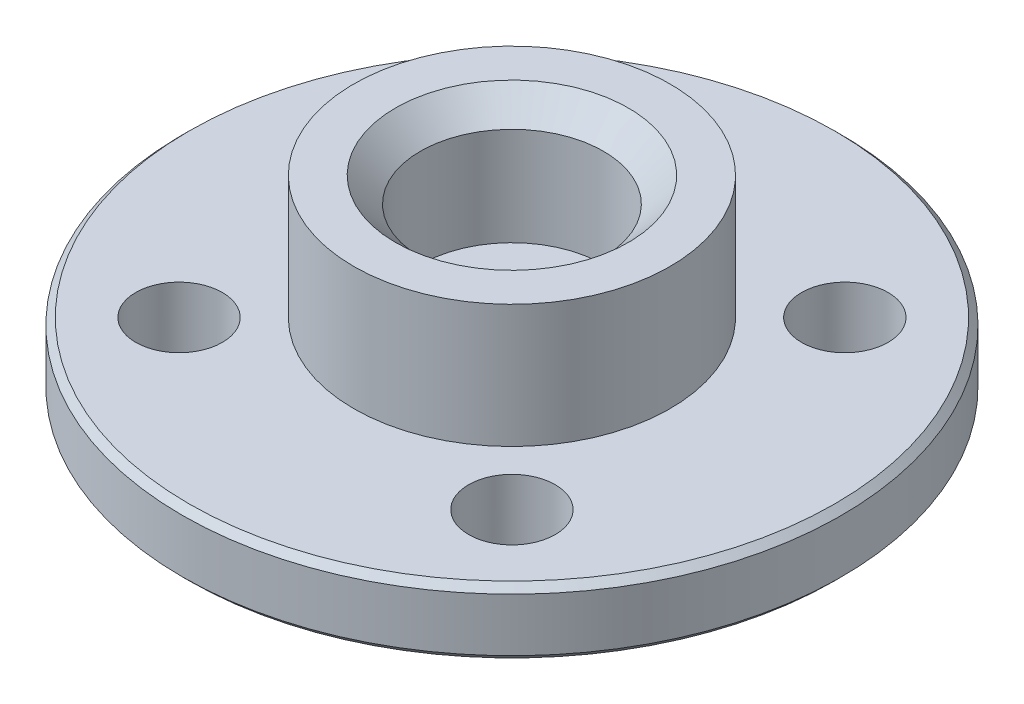
SolidWorks part; units mm, degrees
ref_plane "Front Plane" through (0, 0, 0) normal (0, 0, 1) x (1, 0, 0)
ref_plane "Top Plane" through (0, 0, 0) normal (0, 1, 0) x (1, 0, 0)
ref_plane "Right Plane" through (0, 0, 0) normal (1, 0, 0) x (0, 0, -1)
sketch "Sketch1" plane through (0, 0, 0) normal (0, 1, 0) x (1, 0, 0)
  circle A0 centre (0, 0) radius 9.9
  dimension "D1" = 19.8
extrude "Boss-Extrude1" add sketch "Sketch1" along normal blind 2 contours A0
sketch "Sketch2" plane through (0, 2, 0) normal (0, 1, 0) x (1, 0, 0)
  circle A0 centre (0, 0) radius 4.75
  circle A1 centre (0, 0) radius 2.75
  dimension "D1" = 9.5
  dimension "D2" = 5.5
extrude "Boss-Extrude2" add sketch "Sketch2" along normal blind 3.7
sketch "Sketch3" plane through (0, 0, 0) normal (0, -1, 0) x (1, 0, 0)
  line L0 (-5, 5) -> (5, -5) construction
  line L1 (5, 5) -> (-5, -5) construction
  circle A0 centre (-5, 5) radius 1.3
  circle A1 centre (5, 5) radius 1.3
  circle A2 centre (-5, -5) radius 1.3
  circle A3 centre (5, -5) radius 1.3
  circle A4 centre (0, 0) radius 1.45
  point P11 (0, 0)
  dimension "D1" = 2.9
  dimension "D2" = 2.6
  dimension "D3" = 10
  dimension "D4" = 10
extrude "Cut-Extrude1" cut sketch "Sketch3" against normal up to next
chamfer "Chamfer1" distance 0.75 angle 45 1 edges at (0, 5.7, 2.75)
chamfer "Chamfer2" distance 0.2 angle 45 2 edges at (0, 0, 9.9) (0, 2, 9.9)
